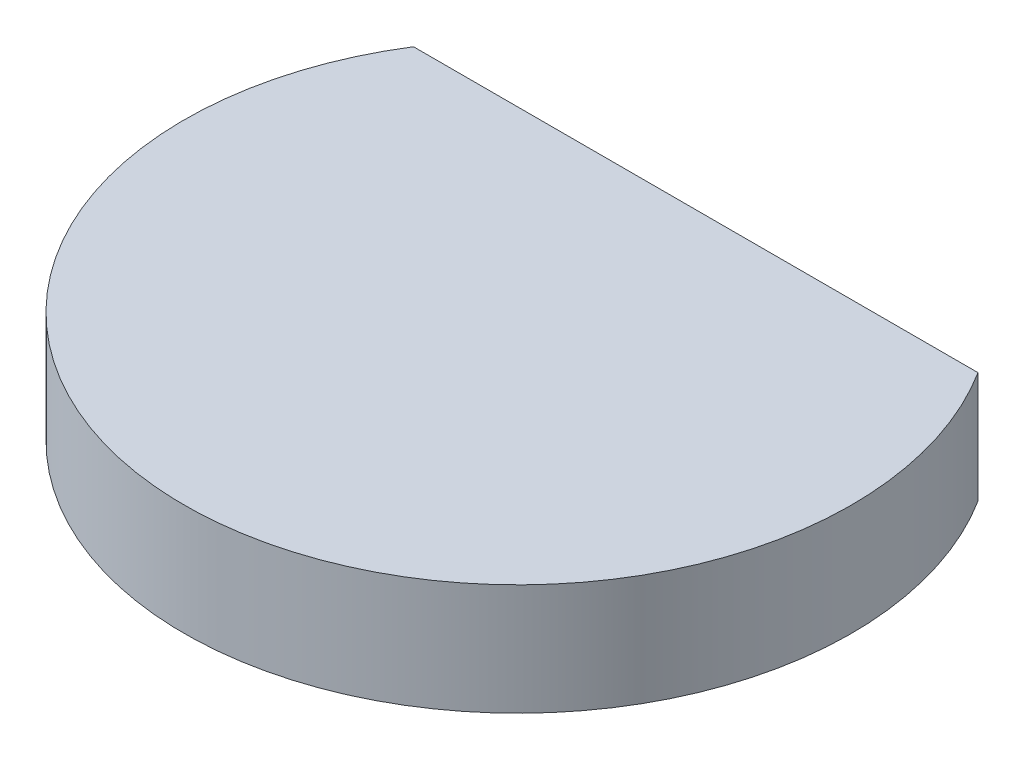
SolidWorks part; units mm, degrees
ref_plane "Front Plane" through (0, 0, 0) normal (0, 0, 1) x (1, 0, 0)
ref_plane "Top Plane" through (0, 0, 0) normal (0, 1, 0) x (1, 0, 0)
ref_plane "Right Plane" through (0, 0, 0) normal (1, 0, 0) x (0, 0, -1)
sketch "Sketch1" plane through (0, 0, 0) normal (0, 1, 0) x (1, 0, 0)
  line L0 (-0.2538, 0.16) -> (0.2538, 0.16)
  line L1 (-0.3, 0) -> (0.3, 0) construction
  line L2 (0, 0) -> (0, 0.16) construction
  line L3 (0, 0) -> (0, -0.3) construction
  arc A0 (-0.2538, 0.16) -> (0.2538, 0.16) centre (0, 0) ccw
  dimension "D1" = 0.6
  dimension "D2" = 0.16
extrude "Boss-Extrude1" add sketch "Sketch1" along normal blind 0.1
